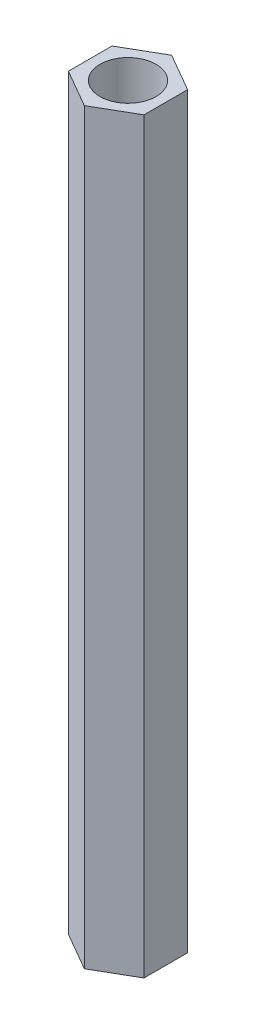
SolidWorks part; units mm, degrees
material "黄铜"
ref_plane "前视基准面" through (0, 0, 0) normal (0, 0, 1) x (1, 0, 0)
ref_plane "上视基准面" through (0, 0, 0) normal (0, 1, 0) x (1, 0, 0)
ref_plane "右视基准面" through (0, 0, 0) normal (1, 0, 0) x (0, 0, -1)
other "Configuration Table"
sketch "草图1" plane through (0, 0, 0) normal (0, 1, 0) x (1, 0, 0)
  line L0 (0, 0) -> (0, 3.0394) construction
  line L1 (2.0222, 1.1675) -> (0, 2.335)
  line L2 (0, 2.335) -> (-2.0222, 1.1675)
  line L3 (-2.0222, 1.1675) -> (-2.0222, -1.1675)
  line L4 (-2.0222, -1.1675) -> (0, -2.335)
  line L5 (0, -2.335) -> (2.0222, -1.1675)
  line L6 (2.0222, -1.1675) -> (2.0222, 1.1675)
  circle A0 centre (0, 0) radius 1.5
  circle A1 centre (0, 0) radius 2.0222 construction
  dimension "D1" = 3
  dimension "D2" = 4.67
extrude "凸台-拉伸1" add sketch "草图1" along normal blind 40
